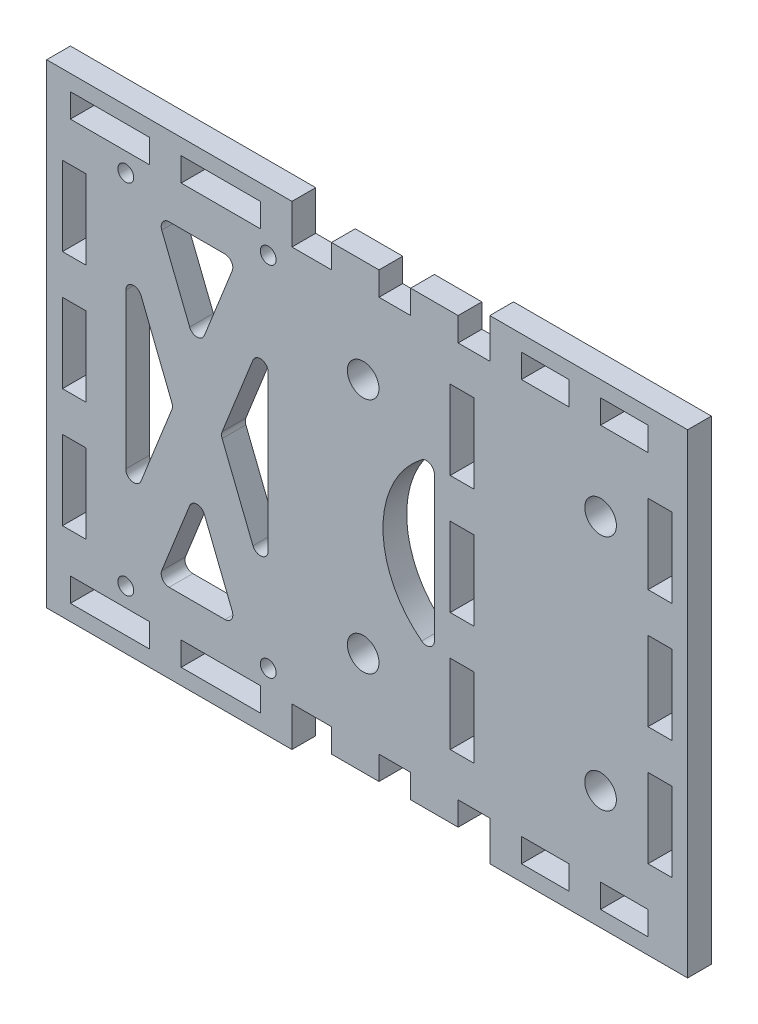
SolidWorks part; units mm, degrees
material "Thornel Mat VMA"
ref_plane "前视基准面" through (0, 0, 0) normal (0, 0, 1) x (1, 0, 0)
ref_plane "上视基准面" through (0, 0, 0) normal (0, 1, 0) x (1, 0, 0)
ref_plane "右视基准面" through (0, 0, 0) normal (1, 0, 0) x (0, 0, -1)
sketch "草图1" plane through (0, 0, 0) normal (0, 0, 1) x (1, 0, 0)
  line L0 (-5, 25) -> (-5, 28)
  line L2 (-20, 25) -> (-20, -25)
  line L4 (25, 20) -> (25, 10)
  line L5 (-20, 25) -> (-15, 25)
  line L6 (-15, 25) -> (-15, 28)
  line L7 (55, 0) -> (-55, 0) construction
  line L8 (0, -55) -> (0, 55) construction
  line L11 (-15, 28) -> (-9, 28)
  line L15 (-5, 28) -> (1, 28)
  line L23 (-20, -25) -> (-20, -28)
  line L32 (25, 5) -> (25, -5)
  line L33 (25, 20) -> (28, 20)
  line L34 (25, 20) -> (25, 10)
  line L35 (25, 10) -> (28, 10)
  line L36 (28, 20) -> (28, 10)
  line L37 (25, 5) -> (28, 5)
  line L38 (28, 5) -> (28, -5)
  line L39 (25, -5) -> (28, -5)
  line L40 (25, -10) -> (25, -20)
  line L41 (25, -10) -> (28, -10)
  line L42 (28, -10) -> (28, -20)
  line L43 (25, -20) -> (28, -20)
  line L44 (25, 25) -> (30, 25)
  line L45 (30, 25) -> (30, -25)
  line L48 (5, 25) -> (10, 25)
  line L49 (20, 25) -> (25, 25)
  line L50 (25, 5) -> (25, -5)
  line L51 (25, -10) -> (25, -20)
  line L55 (3, -5) -> (3, 5)
  line L56 (3, -20) -> (0, -20)
  line L57 (3, -20) -> (3, -10)
  line L58 (3, -10) -> (0, -10)
  line L59 (0, -20) -> (0, -10)
  line L60 (3, -5) -> (0, -5)
  line L61 (0, -5) -> (0, 5)
  line L62 (3, 5) -> (0, 5)
  line L63 (3, 10) -> (3, 20)
  line L64 (3, 10) -> (0, 10)
  line L65 (0, 10) -> (0, 20)
  line L66 (3, 20) -> (0, 20)
  line L67 (5, 25) -> (1, 25)
  line L68 (1, 25) -> (1, 28)
  line L69 (-9, 28) -> (-9, 25)
  line L71 (-9, 25) -> (-5, 25)
  line L72 (10, 28) -> (20, 28) [skipped]
  line L73 (20, 25) -> (10, 25)
  line L74 (25, -25) -> (30, -25)
  line L75 (20, -25) -> (10, -25)
  line L76 (-9, -25) -> (-5, -25)
  line L77 (-9, -28) -> (-9, -25)
  line L78 (1, -25) -> (1, -28)
  line L79 (5, -25) -> (1, -25)
  line L80 (20, -25) -> (25, -25)
  line L81 (5, -25) -> (10, -25)
  line L82 (-5, -28) -> (1, -28)
  line L83 (-15, -28) -> (-9, -28)
  line L84 (-15, -25) -> (-15, -28)
  line L85 (-20, -25) -> (-15, -25)
  line L86 (-5, -25) -> (-5, -28)
  circle A1 centre (-11, 15) radius 2
  circle A2 centre (-11, -15) radius 2
  circle A3 centre (19, -15) radius 2
  circle A4 centre (19, 15) radius 2
  point P0 (0, 0)
  dimension "D1" = 45
  dimension "D3" = 15
  dimension "D4" = 11
  dimension "D5" = 11
  dimension "D10" = 3
  dimension "D11" = 10
  dimension "D12" = 5
  dimension "D14" = 3
  dimension "D15" = 10
  dimension "D16" = 22
  dimension "D17" = 3
  dimension "D18" = 11
  dimension "D9" = 3
  dimension "D13" = 3
extrude "凸台-拉伸1" add sketch "草图1" along normal blind 3
sketch "草图2" plane through (-20, 0, 0) normal (-1, 0, 0) x (0, 0, 1)
  line L6 (1.65, 0) -> (-1.65, 0) construction
  line L7 (0, 30) -> (3, 30)
  line L8 (0, 30) -> (0, -30)
  line L9 (0, -30) -> (3, -30)
  line L10 (3, 30) -> (3, -30)
  line L11 (0, 30) -> (3, -30) construction
  line L12 (0, -30) -> (3, 30) construction
  point P10 (1.5, 0)
  dimension "D1" = 3
  dimension "D2" = 60
extrude "凸台-拉伸2" add sketch "草图2" along normal blind 31
sketch "草图3" plane through (0, 25, 0) normal (0, 1, 0) x (1, 0, 0)
  line L0 (1, -3) -> (30, -3) construction
  line L1 (30, 0) -> (5, 0)
  line L2 (30, 0) -> (30, -3)
  line L3 (30, -3) -> (5, -3)
  line L4 (5, 0) -> (5, -3)
  line L5 (1, -3) -> (1, 0) construction
  dimension "D1" = 4
extrude "凸台-拉伸3" add sketch "草图3" along normal blind 5
mirror "镜向1" about plane through (0, 0, 0) normal (0, 1, 0) of "凸台-拉伸3"
sketch "草图4" plane through (0, 0, 3) normal (0, 0, 1) x (1, 0, 0)
  line L0 (-51, -30) -> (-51, 30) construction
  line L1 (-48, 28) -> (-38, 28)
  line L2 (-48, 28) -> (-48, 25)
  line L3 (-48, 25) -> (-38, 25)
  line L4 (-38, 28) -> (-38, 25)
  line L5 (-48, 28) -> (-38, 25) construction
  line L6 (-48, 25) -> (-38, 28) construction
  line L7 (-51, 30) -> (-20, 30) construction
  line L8 (5, 30) -> (5, 25) construction
  line L9 (-34, 28) -> (-24, 28)
  line L10 (-34, 28) -> (-34, 25)
  line L11 (-34, 25) -> (-24, 25)
  line L12 (-24, 28) -> (-24, 25)
  line L13 (9, 28) -> (15, 28)
  line L14 (9, 28) -> (9, 25)
  line L15 (9, 25) -> (15, 25)
  line L16 (15, 28) -> (15, 25)
  line L17 (19, 28) -> (25, 28)
  line L18 (19, 28) -> (19, 25)
  line L19 (19, 25) -> (25, 25)
  line L20 (25, 28) -> (25, 25)
  line L21 (1.65, 0) -> (-1.65, 0) construction
  line L22 (19, -25) -> (25, -25)
  line L23 (25, -28) -> (25, -25)
  line L24 (19, -28) -> (25, -28)
  line L25 (19, -28) -> (19, -25)
  line L26 (9, -25) -> (15, -25)
  line L27 (15, -28) -> (15, -25)
  line L28 (9, -28) -> (15, -28)
  line L29 (9, -28) -> (9, -25)
  line L30 (-34, -25) -> (-24, -25)
  line L31 (-24, -28) -> (-24, -25)
  line L32 (-34, -28) -> (-24, -28)
  line L33 (-34, -28) -> (-34, -25)
  line L34 (-48, -25) -> (-38, -25)
  line L35 (-38, -28) -> (-38, -25)
  line L36 (-48, -28) -> (-38, -28)
  line L37 (-48, -28) -> (-48, -25)
  line L38 (-49, 5) -> (-49, -5)
  line L39 (-49, 20) -> (-46, 20)
  line L40 (-49, 20) -> (-49, 10)
  line L41 (-49, 10) -> (-46, 10)
  line L42 (-46, 20) -> (-46, 10)
  line L43 (-49, 5) -> (-46, 5)
  line L44 (-46, 5) -> (-46, -5)
  line L45 (-49, -5) -> (-46, -5)
  line L46 (-49, -10) -> (-49, -20)
  line L47 (-49, -10) -> (-46, -10)
  line L48 (-46, -10) -> (-46, -20)
  line L49 (-49, -20) -> (-46, -20)
  point P0 (-43, 26.5)
  dimension "D1" = 3
  dimension "D2" = 3
  dimension "D3" = 2
  dimension "D4" = 10
  dimension "D5" = 4
  dimension "D6" = 4
  dimension "D7" = 4
  dimension "D8" = 2
  dimension "D9" = 3
extrude "切除-拉伸1" cut sketch "草图4" against normal blind 3
sketch "草图5" plane through (0, 0, 0) normal (0, 0, -1) x (-1, 0, 0)
  line L0 (2, 7.3519) -> (2, -7.0559)
  line L1 (0, 1.65) -> (0, -1.65) construction
  line L2 (2, 7.3519) -> (2, 10.9659)
  line L3 (2, -7.0559) -> (2, -10.9659)
  line L4 (23, -15) -> (23, 15)
  line L9 (23, 22.6) -> (41, -22.6) construction
  line L10 (23, -22.6) -> (41, 22.6) construction
  line L11 (1.65, 0) -> (-1.65, 0) construction
  line L12 (23, 15) -> (28.9735, 0)
  line L13 (23, -15) -> (28.9735, 0)
  line L14 (27, -20) -> (32, -7.4444)
  line L15 (41, -15) -> (35.0265, 0)
  line L16 (41, 15) -> (35.0265, 0)
  line L17 (41, -15) -> (41, 15)
  line L18 (27, 20) -> (37, 20)
  line L19 (37, 20) -> (32, 7.4444)
  line L20 (27, 20) -> (32, 7.4444)
  line L21 (37, -20) -> (32, -7.4444)
  line L22 (27, -20) -> (37, -20)
  arc A4 (2, -10.9659) -> (2, 10.9659) centre (-4, 0) ccw
  circle A5 centre (23, 22.6) radius 1
  circle A6 centre (41, 22.6) radius 1
  circle A7 centre (41, -22.6) radius 1
  circle A8 centre (23, -22.6) radius 1
  point P3 (32, 0)
  point P22 (23, 0)
  dimension "D1" = 25
  dimension "D2" = 2
  dimension "D3" = 45.2
  dimension "D4" = 18
extrude "切除-拉伸2" cut sketch "草图5" against normal blind 3
fillet "圆角1" radius 1 14 edges at (-2, 10.9659, 1.5) (-2, -10.9659, 1.5) (-23, 15, 1.5) (-23, -15, 1.5) (-28.9735, 0, 1.5) (-32, -7.4444, 1.5) (-27, -20, 1.5) (-37, -20, 1.5) (-41, -15, 1.5) (-35.0265, 0, 1.5) (-41, 15, 1.5) (-32, 7.4444, 1.5) (-37, 20, 1.5) (-27, 20, 1.5)
